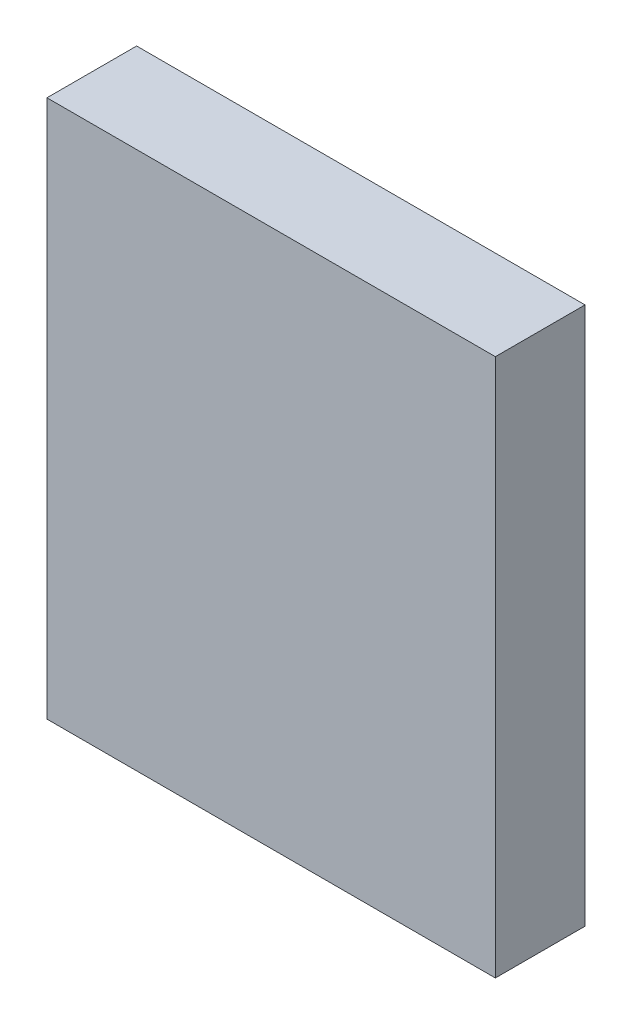
SolidWorks part; units mm, degrees
ref_plane "Front Plane" through (0, 0, 0) normal (0, 0, 1) x (1, 0, 0)
ref_plane "Top Plane" through (0, 0, 0) normal (0, 1, 0) x (1, 0, 0)
ref_plane "Right Plane" through (0, 0, 0) normal (1, 0, 0) x (0, 0, -1)
sketch "Sketch1" plane through (0, 0, 0) normal (0, 0, 1) x (1, 0, 0)
  line L1 (0, 0) -> (50, 0)
  line L2 (0, 0) -> (0, 60)
  line L3 (0, 60) -> (50, 60)
  line L4 (50, 0) -> (50, 60)
  dimension "D1" = 60
  dimension "D2" = 50
extrude "Boss-Extrude1" add sketch "Sketch1" along normal blind 10 contours L2 L1 L4 L3
